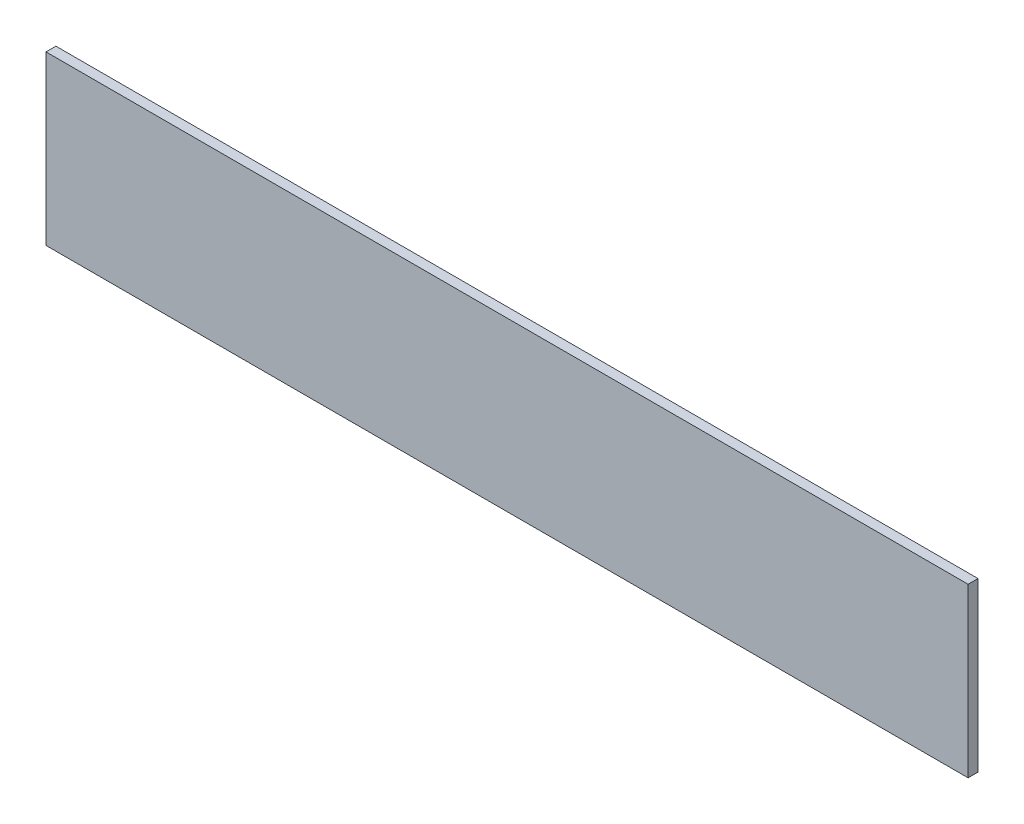
SolidWorks part; units mm, degrees
ref_plane "Front Plane" through (0, 0, 0) normal (0, 0, 1) x (1, 0, 0)
ref_plane "Top Plane" through (0, 0, 0) normal (0, 1, 0) x (1, 0, 0)
ref_plane "Right Plane" through (0, 0, 0) normal (1, 0, 0) x (0, 0, -1)
sketch "Sketch1" plane through (0, 0, 0) normal (0, 0, 1) x (1, 0, 0)
  line L1 (0, 0) -> (279.4, 0)
  line L2 (0, 0) -> (0, 50.8)
  line L3 (0, 50.8) -> (279.4, 50.8)
  line L4 (279.4, 0) -> (279.4, 50.8)
  dimension "D1" = 279.4
  dimension "D2" = 50.8
extrude "Boss-Extrude1" add sketch "Sketch1" along normal blind 3
